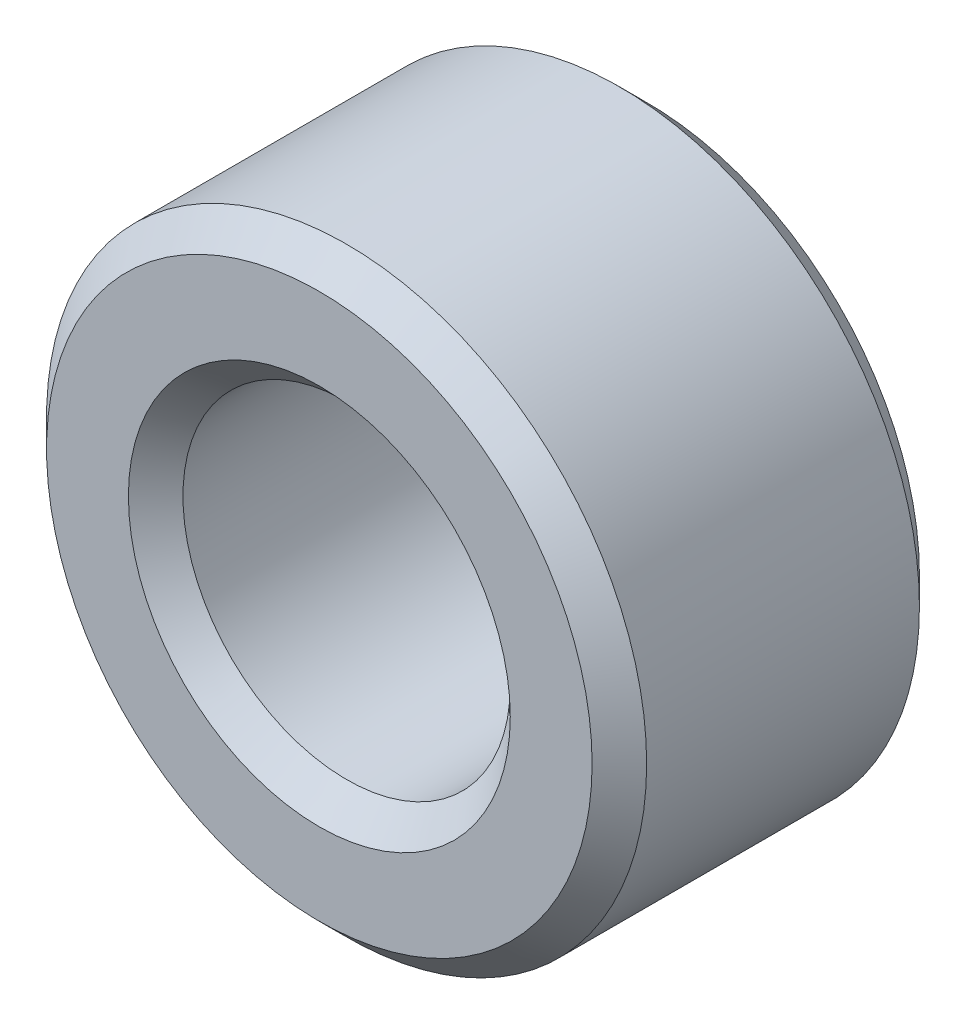
SolidWorks part; units mm, degrees
material "1.5918 (17CrNi6-6)"
ref_plane "Přední rovina" through (0, 0, 0) normal (0, 0, 1) x (1, 0, 0)
ref_plane "Horní rovina" through (0, 0, 0) normal (0, 1, 0) x (1, 0, 0)
ref_plane "Pravá rovina" through (0, 0, 0) normal (1, 0, 0) x (0, 0, -1)
sketch "Skica1" plane through (0, 0, 0) normal (0, 0, 1) x (1, 0, 0)
  circle A0 centre (0, 0) radius 3
  circle A1 centre (0, 0) radius 5.5
  dimension "D1" = 6
  dimension "D2" = 11
extrude "Přidat vysunutím1" add sketch "Skica1" along normal blind 6
chamfer "Zkosení1" distance 0.5 angle 45 4 edges at (3, 0, 6) (3, 0, 0) (5.5, 0, 0) (5.5, 0, 6)
